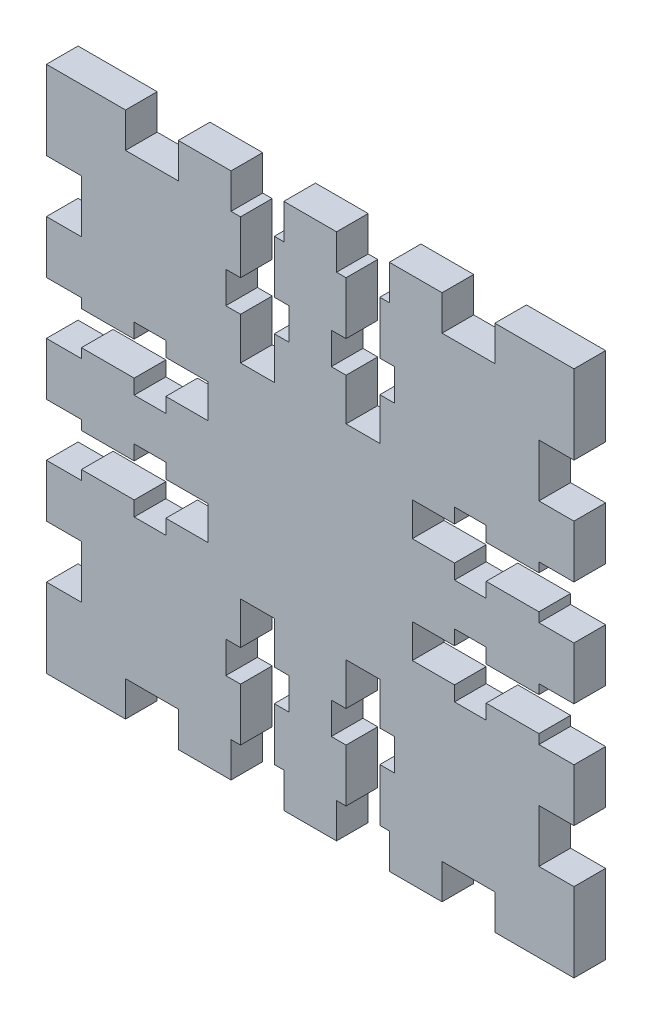
SolidWorks part; units mm, degrees
ref_plane "Plan de face" through (0, 0, 0) normal (0, 0, 1) x (1, 0, 0)
ref_plane "Plan de dessus" through (0, 0, 0) normal (0, 1, 0) x (1, 0, 0)
ref_plane "Plan de droite" through (0, 0, 0) normal (1, 0, 0) x (0, 0, -1)
sketch "Sketch1" plane through (0, 0, 0) normal (0, 0, 1) x (1, 0, 0)
  line L1 (-21.2669, 15.852) -> (28.7331, 15.852)
  line L2 (-21.2669, 15.852) -> (-21.2669, -34.148)
  line L3 (-21.2669, -34.148) -> (28.7331, -34.148)
  line L4 (28.7331, 15.852) -> (28.7331, -34.148)
  dimension "D1" = 50
  dimension "D2" = 50
extrude "Boss-Extrude1" add sketch "Sketch1" along normal blind 3
sketch "Sketch2" plane through (0, 0, 3) normal (0, 0, 1) x (1, 0, 0)
  line L0 (28.7331, 15.852) -> (-21.2669, 15.852) construction
  line L1 (-13.7669, 15.852) -> (-8.7669, 15.852)
  line L2 (-13.7669, 15.852) -> (-13.7669, 12.5316)
  line L3 (-13.7669, 12.5316) -> (-8.7669, 12.5316)
  line L4 (-8.7669, 15.852) -> (-8.7669, 12.5316)
  line L5 (-21.2669, 15.852) -> (-21.2669, -34.148) construction
  line L6 (6.2331, 15.852) -> (6.2331, 12.5316)
  line L7 (-3.7669, 15.852) -> (1.2331, 15.852)
  line L8 (-3.7669, 15.852) -> (-3.7669, 12.5316)
  line L9 (-3.7669, 12.5316) -> (1.2331, 12.5316)
  line L10 (1.2331, 15.852) -> (1.2331, 12.5316)
  line L11 (6.2331, 15.852) -> (11.2331, 15.852)
  line L12 (11.2331, 15.852) -> (11.2331, 12.5316)
  line L13 (6.2331, 12.5316) -> (11.2331, 12.5316)
  line L14 (16.2331, 15.852) -> (16.2331, 12.5316)
  line L15 (16.2331, 15.852) -> (21.2331, 15.852)
  line L16 (21.2331, 15.852) -> (21.2331, 12.5316)
  line L17 (16.2331, 12.5316) -> (21.2331, 12.5316)
  line L18 (28.7331, 8.352) -> (25.4127, 8.352)
  line L19 (-21.2669, 15.852) -> (28.7331, -34.148) construction
  line L20 (28.7331, 15.852) -> (-21.2669, -34.148) construction
  line L21 (28.7331, 8.352) -> (28.7331, 3.352)
  line L22 (28.7331, 3.352) -> (25.4127, 3.352)
  line L23 (25.4127, 8.352) -> (25.4127, 3.352)
  line L24 (28.7331, -1.648) -> (25.4127, -1.648)
  line L25 (28.7331, -1.648) -> (28.7331, -6.648)
  line L26 (28.7331, -6.648) -> (25.4127, -6.648)
  line L27 (25.4127, -1.648) -> (25.4127, -6.648)
  line L28 (28.7331, -11.648) -> (25.4127, -11.648)
  line L29 (25.4127, -11.648) -> (25.4127, -16.648)
  line L30 (28.7331, -16.648) -> (25.4127, -16.648)
  line L31 (28.7331, -11.648) -> (28.7331, -16.648)
  line L32 (28.7331, -21.648) -> (25.4127, -21.648)
  line L33 (25.4127, -21.648) -> (25.4127, -26.648)
  line L34 (28.7331, -26.648) -> (25.4127, -26.648)
  line L35 (28.7331, -21.648) -> (28.7331, -26.648)
  line L36 (21.2331, -34.148) -> (21.2331, -30.8277)
  line L37 (21.2331, -34.148) -> (16.2331, -34.148)
  line L38 (16.2331, -34.148) -> (16.2331, -30.8277)
  line L39 (21.2331, -30.8277) -> (16.2331, -30.8277)
  line L40 (11.2331, -34.148) -> (11.2331, -30.8277)
  line L41 (11.2331, -34.148) -> (6.2331, -34.148)
  line L42 (6.2331, -34.148) -> (6.2331, -30.8277)
  line L43 (11.2331, -30.8277) -> (6.2331, -30.8277)
  line L44 (1.2331, -34.148) -> (1.2331, -30.8277)
  line L45 (1.2331, -30.8277) -> (-3.7669, -30.8277)
  line L46 (-3.7669, -34.148) -> (-3.7669, -30.8277)
  line L47 (1.2331, -34.148) -> (-3.7669, -34.148)
  line L48 (-8.7669, -34.148) -> (-8.7669, -30.8277)
  line L49 (-8.7669, -30.8277) -> (-13.7669, -30.8277)
  line L50 (-13.7669, -34.148) -> (-13.7669, -30.8277)
  line L51 (-8.7669, -34.148) -> (-13.7669, -34.148)
  line L52 (-21.2669, -26.648) -> (-17.9466, -26.648)
  line L53 (-21.2669, -26.648) -> (-21.2669, -21.648)
  line L54 (-21.2669, -21.648) -> (-17.9466, -21.648)
  line L55 (-17.9466, -26.648) -> (-17.9466, -21.648)
  line L56 (-21.2669, -16.648) -> (-17.9466, -16.648)
  line L57 (-21.2669, -16.648) -> (-21.2669, -11.648)
  line L58 (-21.2669, -11.648) -> (-17.9466, -11.648)
  line L59 (-17.9466, -16.648) -> (-17.9466, -11.648)
  line L60 (-21.2669, -6.648) -> (-17.9466, -6.648)
  line L61 (-17.9466, -6.648) -> (-17.9466, -1.648)
  line L62 (-21.2669, -1.648) -> (-17.9466, -1.648)
  line L63 (-21.2669, -6.648) -> (-21.2669, -1.648)
  line L64 (-21.2669, 3.352) -> (-17.9466, 3.352)
  line L65 (-17.9466, 3.352) -> (-17.9466, 8.352)
  line L66 (-21.2669, 8.352) -> (-17.9466, 8.352)
  line L67 (-21.2669, 3.352) -> (-21.2669, 8.352)
  point P12 (-8.7669, 14.1918)
  point P29 (3.7331, -9.148)
  point P81 (3.7331, -9.148)
  dimension "D1" = 7.5
  dimension "D2" = 5
  dimension "D3" = 5
  dimension "D4" = 5
  dimension "D6" = 4
  dimension "D5" = 3
extrude "Cut-Extrude1" cut sketch "Sketch2" against normal blind 3
sketch "Sketch4" plane through (0, 12.5316, 0) normal (0, 1, 0) x (1, 0, 0)
  line L0 (-3.7669, 0) -> (1.2331, -3) construction
  line L1 (6.2331, 0) -> (11.2331, -3) construction
  line L2 (6.2331, -3) -> (11.2331, -3) construction
  line L3 (-3.7669, 0) -> (1.2331, 0) construction
  line L4 (0.3331, -3) -> (-2.8669, -3)
  line L5 (0.3331, -3) -> (0.3331, 0)
  line L6 (0.3331, 0) -> (-2.8669, 0)
  line L7 (-2.8669, -3) -> (-2.8669, 0)
  line L8 (0.3331, -3) -> (-2.8669, 0) construction
  line L9 (0.3331, 0) -> (-2.8669, -3) construction
  line L10 (6.2331, 0) -> (11.2331, 0) construction
  line L11 (10.3331, -3) -> (7.1331, -3)
  line L12 (10.3331, -3) -> (10.3331, 0)
  line L13 (10.3331, 0) -> (7.1331, 0)
  line L14 (7.1331, -3) -> (7.1331, 0)
  line L15 (10.3331, -3) -> (7.1331, 0) construction
  line L16 (10.3331, 0) -> (7.1331, -3) construction
  point P9 (-1.2669, -1.5)
  point P16 (8.7331, -1.5)
  dimension "D1" = 3.2
  dimension "D2" = 3.2
extrude "Cut-Extrude2" cut sketch "Sketch4" against normal blind 12
sketch "Sketch5" plane through (25.4127, 0, 0) normal (1, 0, 0) x (0, 0, -1)
  line L0 (0, -6.648) -> (-3, -1.648) construction
  line L1 (0, -1.648) -> (-3, -6.648) construction
  line L2 (0, -1.648) -> (0, -6.648) construction
  line L3 (-3, -5.748) -> (0, -5.748)
  line L4 (-3, -5.748) -> (-3, -2.548)
  line L5 (-3, -2.548) -> (0, -2.548)
  line L6 (0, -5.748) -> (0, -2.548)
  line L7 (-3, -5.748) -> (0, -2.548) construction
  line L8 (-3, -2.548) -> (0, -5.748) construction
  line L9 (-3, -15.748) -> (-3, -12.548)
  line L10 (-3, -15.748) -> (0, -15.748)
  line L11 (0, -15.748) -> (0, -12.548)
  line L12 (-3, -12.548) -> (0, -12.548)
  point P8 (-1.5, -4.148)
  dimension "D1" = 3.2
  dimension "D2" = 2
extrude "Cut-Extrude3" cut sketch "Sketch5" against normal blind 12
sketch "Sketch6" plane through (0, -30.8277, 0) normal (0, -1, 0) x (1, 0, 0)
  line L0 (-3.7669, 0) -> (1.2331, 3) construction
  line L1 (1.2331, 0) -> (-3.7669, 0) construction
  line L2 (0.3331, 3) -> (-2.8669, 3)
  line L3 (0.3331, 3) -> (0.3331, 0)
  line L4 (0.3331, 0) -> (-2.8669, 0)
  line L5 (-2.8669, 3) -> (-2.8669, 0)
  line L6 (0.3331, 3) -> (-2.8669, 0) construction
  line L7 (0.3331, 0) -> (-2.8669, 3) construction
  line L8 (10.3331, 0) -> (7.1331, 3) construction
  line L9 (10.3331, 3) -> (10.3331, 0)
  line L10 (10.3331, 3) -> (7.1331, 3)
  line L11 (7.1331, 3) -> (7.1331, 0)
  line L12 (10.3331, 0) -> (7.1331, 0)
  point P4 (-1.2669, 1.5)
  dimension "D1" = 3.2
  dimension "D2" = 2
extrude "Cut-Extrude4" cut sketch "Sketch6" against normal blind 12
ref_plane "Plane1" through (-17.9466, -16.648, 0) normal (0, 1, 0) x (1, 0, 0)
sketch "Sketch8" plane through (-17.9466, 0, 0) normal (-1, 0, 0) x (0, 0, 1)
  line L0 (0, -16.648) -> (3, -11.648) construction
  line L1 (0, -16.648) -> (0, -11.648) construction
  line L2 (3, -12.548) -> (0, -12.548)
  line L3 (3, -12.548) -> (3, -15.748)
  line L4 (3, -15.748) -> (0, -15.748)
  line L5 (0, -12.548) -> (0, -15.748)
  line L6 (3, -12.548) -> (0, -15.748) construction
  line L7 (3, -15.748) -> (0, -12.548) construction
  line L8 (3, -2.548) -> (3, -5.748)
  line L9 (3, -2.548) -> (0, -2.548)
  line L10 (0, -2.548) -> (0, -5.748)
  line L11 (3, -5.748) -> (0, -5.748)
  point P4 (1.5, -14.148)
  dimension "D1" = 3.2
  dimension "D2" = 2
extrude "Cut-Extrude5" cut sketch "Sketch8" against normal blind 12
sketch "Sketch9" plane through (0, 0, 0) normal (0, 0, -1) x (-1, 0, 0)
  line L0 (-11.2331, -30.8277) -> (-10.3331, -30.8277) construction
  line L1 (-11.7331, -25.8277) -> (-5.7331, -25.8277)
  line L2 (-11.7331, -25.8277) -> (-11.7331, -22.8277)
  line L3 (-11.7331, -22.8277) -> (-5.7331, -22.8277)
  line L4 (-5.7331, -25.8277) -> (-5.7331, -22.8277)
  line L5 (-10.3331, -18.8277) -> (-10.3331, -30.8277) construction
  line L6 (-1.7331, -25.8277) -> (-1.7331, -22.8277)
  line L7 (-1.7331, -25.8277) -> (4.2669, -25.8277)
  line L8 (4.2669, -25.8277) -> (4.2669, -22.8277)
  line L9 (-1.7331, -22.8277) -> (4.2669, -22.8277)
  line L10 (-28.7331, -34.148) -> (21.2669, 15.852) construction
  line L11 (-20.4127, -1.148) -> (-17.4127, -1.148)
  line L12 (-20.4127, -1.148) -> (-20.4127, -7.148)
  line L13 (-20.4127, -7.148) -> (-17.4127, -7.148)
  line L14 (-17.4127, -1.148) -> (-17.4127, -7.148)
  line L15 (-20.4127, -11.148) -> (-17.4127, -11.148)
  line L16 (-17.4127, -11.148) -> (-17.4127, -17.148)
  line L17 (-20.4127, -17.148) -> (-17.4127, -17.148)
  line L18 (-20.4127, -11.148) -> (-20.4127, -17.148)
  line L19 (4.2669, 7.5316) -> (4.2669, 4.5316)
  line L20 (4.2669, 7.5316) -> (-1.7331, 7.5316)
  line L21 (-1.7331, 7.5316) -> (-1.7331, 4.5316)
  line L22 (4.2669, 4.5316) -> (-1.7331, 4.5316)
  line L23 (-5.7331, 7.5316) -> (-5.7331, 4.5316)
  line L24 (-5.7331, 4.5316) -> (-11.7331, 4.5316)
  line L25 (-11.7331, 7.5316) -> (-11.7331, 4.5316)
  line L26 (-5.7331, 7.5316) -> (-11.7331, 7.5316)
  line L27 (12.9466, -17.148) -> (9.9466, -17.148)
  line L28 (12.9466, -17.148) -> (12.9466, -11.148)
  line L29 (12.9466, -11.148) -> (9.9466, -11.148)
  line L30 (9.9466, -17.148) -> (9.9466, -11.148)
  line L31 (12.9466, -7.148) -> (9.9466, -7.148)
  line L32 (9.9466, -7.148) -> (9.9466, -1.148)
  line L33 (12.9466, -1.148) -> (9.9466, -1.148)
  line L34 (12.9466, -7.148) -> (12.9466, -1.148)
  point P16 (-3.7331, -9.148)
  point P17 (0, 0)
  point P18 (-3.4687, -8.8837)
  point P44 (-3.7331, -9.148)
  dimension "D1" = 6
  dimension "D2" = 3
  dimension "D3" = 5
  dimension "D4" = 1.4
  dimension "D7" = 0
  dimension "D5" = 2
  dimension "D6" = 4
extrude "Cut-Extrude6" cut sketch "Sketch9" against normal blind 12
